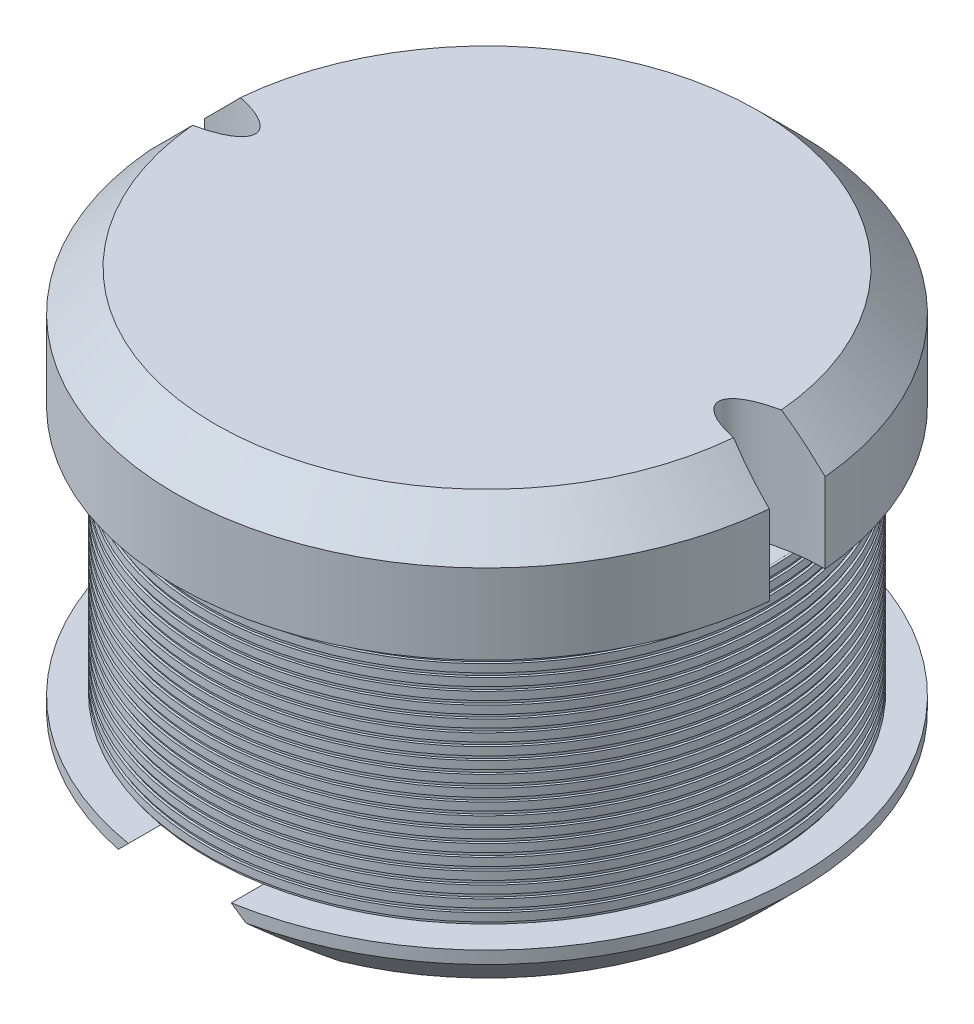
SolidWorks part; units mm, degrees
ref_plane "Front Plane" through (0, 0, 0) normal (0, 0, 1) x (1, 0, 0)
ref_plane "Top Plane" through (0, 0, 0) normal (0, 1, 0) x (1, 0, 0)
ref_plane "Right Plane" through (0, 0, 0) normal (1, 0, 0) x (0, 0, -1)
sketch "Sketch1" plane through (0, 0, 0) normal (0, 1, 0) x (1, 0, 0)
  circle A0 centre (0, 0) radius 3.9
  dimension "D1" = 7.8
extrude "Boss-Extrude1" add sketch "Sketch1" along normal blind 5.3
sketch "Sketch2" plane through (0, 0, 0) normal (0, 0, 1) x (1, 0, 0)
  line L0 (0, 0) -> (-1.3, 0)
  line L1 (-3.9, 0) -> (3.9, 0) construction
  line L2 (-1.3, 0) -> (-0.6437, 0.6563)
  line L3 (-0.6437, 0.6563) -> (0.6437, 0.6563)
  line L4 (0.6437, 0.6563) -> (1.3, 0)
  line L5 (1.3, 0) -> (0, 0)
  dimension "D1" = 2.6
  dimension "D2" = 1.3
  dimension "D3" = 45
  dimension "D4" = 45
chamfer "Chamfer1" distance 0.5 angle 45 1 edges at (0, 5.3, 3.9)
chamfer "Chamfer2" distance 0.5 angle 45 1 edges at (0, 0, 3.9)
extrude "Cut-Extrude2" cut sketch "Sketch2" against normal through all both and the other way through all
sketch "Sketch4" plane through (0, 5.3, 0) normal (0, 1, 0) x (1, 0, 0)
  line L0 (0, -1000) -> (0, 49000) construction
  line L1 (-1000, 0) -> (49000, 0) construction
  circle A0 centre (0, 0) radius 3.9 construction
  ellipse E0 centre (-3.9, 0) end of major axis (-4.9, 0) minor radius 0.35
  ellipse E1 centre (3.9, 0) end of major axis (4.9, 0) minor radius 0.35
  dimension "D1" = 1
  dimension "D2" = 0.7
extrude "Cut-Extrude4" cut sketch "Sketch4" against normal blind 1.5
sketch "Sketch5" plane through (0, 0, 0) normal (0, 0, 1) x (1, 0, 0)
  line L0 (0, -1000) -> (0, 49000) construction
  line L1 (-1003.8843, 3.8) -> (48996.1157, 3.8) construction
  line L2 (-1000.6437, 0.6563) -> (48999.3563, 0.6563) construction
  line L3 (-3.9, 3.8) -> (-3.9, 0.5) construction
  line L4 (-4.3, 3.8) -> (-3.5, 3.8)
  line L5 (-4.3, 3.8) -> (-4.3, 0.6563)
  line L6 (-4.3, 0.6563) -> (-3.5, 0.6563)
  line L7 (-3.5, 3.8) -> (-3.5, 0.6563)
  dimension "D1" = 0.4
  dimension "D2" = 0.4
revolve "Cut-Revolve1" cut sketch "Sketch5" angle 360 about L0
sketch "Sketch6" plane through (0, 0, 0) normal (0, 0, 1) x (1, 0, 0)
  line L0 (-3.53, 3.65) -> (-3.53, 3.55)
  line L1 (-3.5, 3.8) -> (-3.53, 3.8)
  line L2 (-3.5, 3.8) -> (-3.5, 3.7)
  line L3 (-3.5, 3.7) -> (-3.53, 3.7)
  line L4 (-3.53, 3.8) -> (-3.53, 3.7)
  line L5 (-3.5, 3.55) -> (-3.53, 3.55)
  line L6 (-3.5, 3.65) -> (-3.5, 3.55)
  line L7 (-3.5, 3.65) -> (-3.53, 3.65)
  line L8 (-3.53, 3.5) -> (-3.53, 3.4)
  line L9 (-3.5, 3.4) -> (-3.53, 3.4)
  line L10 (-3.5, 3.5) -> (-3.5, 3.4)
  line L11 (-3.5, 3.5) -> (-3.53, 3.5)
  line L12 (-3.53, 3.35) -> (-3.53, 3.25)
  line L13 (-3.5, 3.25) -> (-3.53, 3.25)
  line L14 (-3.5, 3.35) -> (-3.5, 3.25)
  line L15 (-3.5, 3.35) -> (-3.53, 3.35)
  line L16 (-3.53, 3.2) -> (-3.53, 3.1)
  line L17 (-3.5, 3.1) -> (-3.53, 3.1)
  line L18 (-3.5, 3.2) -> (-3.5, 3.1)
  line L19 (-3.5, 3.2) -> (-3.53, 3.2)
  line L20 (-3.53, 3.05) -> (-3.53, 2.95)
  line L21 (-3.5, 2.95) -> (-3.53, 2.95)
  line L22 (-3.5, 3.05) -> (-3.5, 2.95)
  line L23 (-3.5, 3.05) -> (-3.53, 3.05)
  line L24 (-3.53, 2.9) -> (-3.53, 2.8)
  line L25 (-3.5, 2.8) -> (-3.53, 2.8)
  line L26 (-3.5, 2.9) -> (-3.5, 2.8)
  line L27 (-3.5, 2.9) -> (-3.53, 2.9)
  line L28 (-3.53, 2.75) -> (-3.53, 2.65)
  line L29 (-3.5, 2.65) -> (-3.53, 2.65)
  line L30 (-3.5, 2.75) -> (-3.5, 2.65)
  line L31 (-3.5, 2.75) -> (-3.53, 2.75)
  line L32 (-3.53, 2.6) -> (-3.53, 2.5)
  line L33 (-3.5, 2.5) -> (-3.53, 2.5)
  line L34 (-3.5, 2.6) -> (-3.5, 2.5)
  line L35 (-3.5, 2.6) -> (-3.53, 2.6)
  line L36 (-3.53, 2.45) -> (-3.53, 2.35)
  line L37 (-3.5, 2.35) -> (-3.53, 2.35)
  line L38 (-3.5, 2.45) -> (-3.5, 2.35)
  line L39 (-3.5, 2.45) -> (-3.53, 2.45)
  line L40 (-3.53, 2.3) -> (-3.53, 2.2)
  line L41 (-3.5, 2.2) -> (-3.53, 2.2)
  line L42 (-3.5, 2.3) -> (-3.5, 2.2)
  line L43 (-3.5, 2.3) -> (-3.53, 2.3)
  line L44 (-3.53, 2.15) -> (-3.53, 2.05)
  line L45 (-3.5, 2.05) -> (-3.53, 2.05)
  line L46 (-3.5, 2.15) -> (-3.5, 2.05)
  line L47 (-3.5, 2.15) -> (-3.53, 2.15)
  line L48 (-3.53, 2) -> (-3.53, 1.9)
  line L49 (-3.5, 1.9) -> (-3.53, 1.9)
  line L50 (-3.5, 2) -> (-3.5, 1.9)
  line L51 (-3.5, 2) -> (-3.53, 2)
  line L52 (-3.53, 1.85) -> (-3.53, 1.75)
  line L53 (-3.5, 1.75) -> (-3.53, 1.75)
  line L54 (-3.5, 1.85) -> (-3.5, 1.75)
  line L55 (-3.5, 1.85) -> (-3.53, 1.85)
  line L56 (-3.53, 1.7) -> (-3.53, 1.6)
  line L57 (-3.5, 1.6) -> (-3.53, 1.6)
  line L58 (-3.5, 1.7) -> (-3.5, 1.6)
  line L59 (-3.5, 1.7) -> (-3.53, 1.7)
  line L60 (-3.53, 1.55) -> (-3.53, 1.45)
  line L61 (-3.5, 1.45) -> (-3.53, 1.45)
  line L62 (-3.5, 1.55) -> (-3.5, 1.45)
  line L63 (-3.5, 1.55) -> (-3.53, 1.55)
  line L64 (-3.53, 1.4) -> (-3.53, 1.3)
  line L65 (-3.5, 1.3) -> (-3.53, 1.3)
  line L66 (-3.5, 1.4) -> (-3.5, 1.3)
  line L67 (-3.5, 1.4) -> (-3.53, 1.4)
  line L68 (-3.53, 1.25) -> (-3.53, 1.15)
  line L69 (-3.5, 1.15) -> (-3.53, 1.15)
  line L70 (-3.5, 1.25) -> (-3.5, 1.15)
  line L71 (-3.5, 1.25) -> (-3.53, 1.25)
  line L72 (-3.53, 1.1) -> (-3.53, 1)
  line L73 (-3.5, 1) -> (-3.53, 1)
  line L74 (-3.5, 1.1) -> (-3.5, 1)
  line L75 (-3.5, 1.1) -> (-3.53, 1.1)
  line L76 (-3.53, 0.95) -> (-3.53, 0.85)
  line L77 (-3.5, 0.85) -> (-3.53, 0.85)
  line L78 (-3.5, 0.95) -> (-3.5, 0.85)
  line L79 (-3.5, 0.95) -> (-3.53, 0.95)
  line L80 (-3.53, 0.8) -> (-3.53, 0.7)
  line L81 (-3.5, 0.7) -> (-3.53, 0.7)
  line L82 (-3.5, 0.8) -> (-3.5, 0.7)
  line L83 (-3.5, 0.8) -> (-3.53, 0.8)
  line L84 (0, -1000) -> (0, 49000) construction
  dimension "D1" = 0.1
  dimension "D2" = 0.03
  dimension "D3" = 21
revolve "Revolve1" add sketch "Sketch6" angle 360 about L84
equation "\"D2@Sketch2\"=\"D1@Sketch2\"/2"
equation "\"D2@Sketch5\"=\"D1@Sketch5\""
